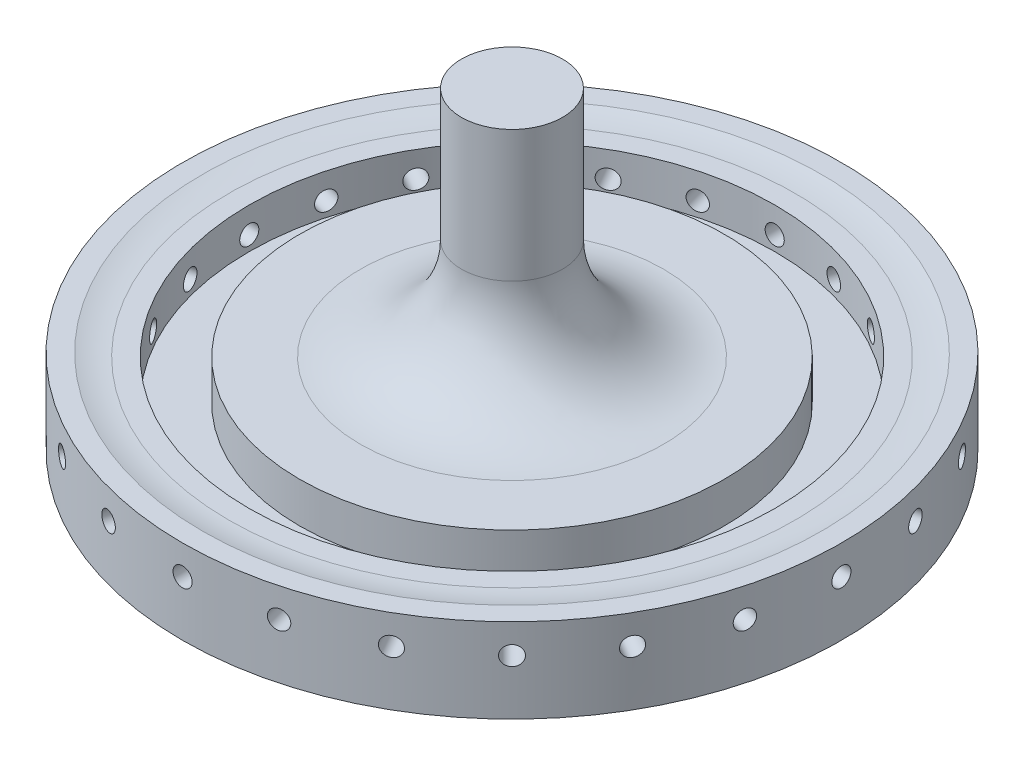
SolidWorks part; units mm, degrees
ref_plane "Front Plane" through (0, 0, 0) normal (0, 0, 1) x (1, 0, 0)
ref_plane "Top Plane" through (0, 0, 0) normal (0, 1, 0) x (1, 0, 0)
ref_plane "Right Plane" through (0, 0, 0) normal (1, 0, 0) x (0, 0, -1)
sketch "Sketch1" plane through (0, 0, 0) normal (0, 0, 1) x (1, 0, 0)
  line L0 (0, 0) -> (0, -33.5996) construction
  line L1 (0, 0) -> (3.175, 0)
  line L2 (3.175, 0) -> (3.175, -8.255)
  line L4 (9.525, -14.605) -> (13.335, -14.605)
  line L7 (20.6935, -19.685) -> (0, -19.685)
  line L8 (0, -19.685) -> (0, 0)
  line L9 (19.4235, -14.3886) -> (20.6935, -14.3886)
  line L10 (20.6935, -14.3886) -> (20.6935, -19.685)
  line L12 (19.4235, -14.3886) -> (23.7588, -13.227) construction
  line L13 (16.51, -14.605) -> (16.51, -17.145)
  line L14 (16.51, -17.145) -> (13.335, -17.145)
  line L15 (13.335, -17.145) -> (13.335, -14.605)
  line L16 (16.51, -14.605) -> (17.78, -14.605)
  arc A0 (17.78, -14.605) -> (19.4235, -14.3886) centre (17.78, -8.255) ccw
  arc A1 (3.175, -8.255) -> (9.525, -14.605) centre (9.525, -8.255) ccw
  dimension "D8" = 3.175
  dimension "D2" = 6.35
  dimension "D1" = 8.255
  dimension "D3" = 6.35
  dimension "D4" = 8.255
  dimension "D5" = 1.27
  dimension "D6" = 15
  dimension "D7" = 5.08
  dimension "D9" = 1.27
  dimension "D10" = 2.54
revolve "Revolve1" add sketch "Sketch1" angle 360 about L0
ref_plane "Plane1" through (0, 0, 20.6935) normal (0, 0, 1) x (1, 0, 0)
sketch "Sketch2" plane through (0, 0, 20.6935) normal (0, 0, 1) x (1, 0, 0)
  line L0 (16.51, -17.145) -> (-16.51, -17.145) construction
  line L1 (16.51, -17.145) -> (-16.51, -17.145) construction
  circle A0 centre (0, -16.2275) radius 0.6
  point P5 (0, -16.137)
  dimension "D1" = 1.2
  dimension "D2" = 0.635
extrude "Cut-Extrude1" cut sketch "Sketch2" against normal up to next
pattern_circular "CirPattern1" count 24 over 360 about axis through (0, -14.3886, 0) along (0, 1, 0) of "Cut-Extrude1"
